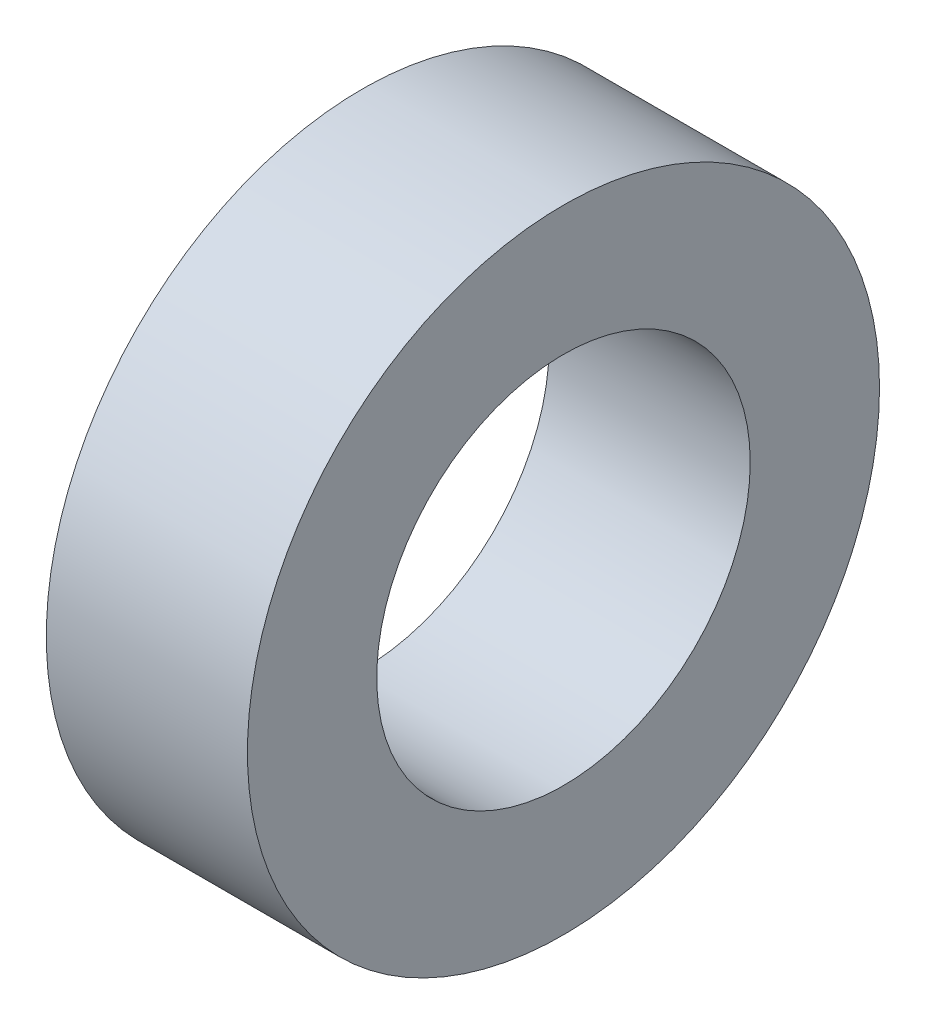
SolidWorks part; units mm, degrees
ref_plane "前视基准面" through (0, 0, 0) normal (0, 0, 1) x (1, 0, 0)
ref_plane "上视基准面" through (0, 0, 0) normal (0, 1, 0) x (1, 0, 0)
ref_plane "右视基准面" through (0, 0, 0) normal (1, 0, 0) x (0, 0, -1)
sketch "草图1" plane through (0, 0, 0) normal (1, 0, 0) x (0, 0, -1)
  circle A0 centre (0, 0) radius 11
  circle A1 centre (0, 0) radius 6.5
  dimension "D1" = 13
  dimension "D2" = 22
extrude "凸台-拉伸1" add sketch "草图1" along normal blind 7
